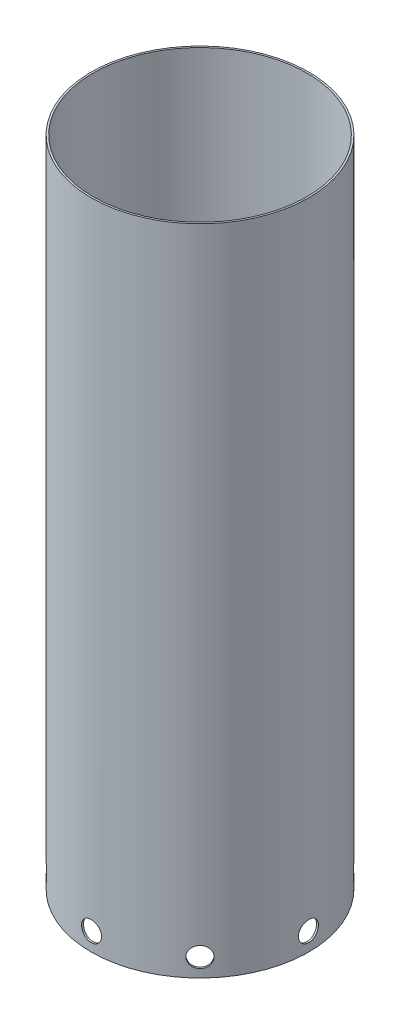
SolidWorks part; units mm, degrees
ref_plane "Front Plane" through (0, 0, 0) normal (0, 0, 1) x (1, 0, 0)
ref_plane "Top Plane" through (0, 0, 0) normal (0, 1, 0) x (1, 0, 0)
ref_plane "Right Plane" through (0, 0, 0) normal (1, 0, 0) x (0, 0, -1)
sketch "Sketch2" plane through (0, 0, 0) normal (0, 1, 0) x (1, 0, 0)
  circle A0 centre (0, 0) radius 74.93
  circle A1 centre (0, 0) radius 76.2
  dimension "D1" = 152.4
  dimension "D2" = 1.27
extrude "Boss-Extrude1" add sketch "Sketch2" along normal blind 457.2
sketch "Sketch3" plane through (0, 101.6, 0) normal (1, 0, 0) x (0, 0, -1)
  circle A0 centre (0, -38.1) radius 5.715 construction
  circle A1 centre (0, -38.1) radius 5.715 construction
  circle A2 centre (0, -38.1) radius 6.985
  dimension "D1" = 1.27
extrude "LOX to Kero, LOX Side Holes" [suppressed] cut sketch "Sketch3" along normal up to surface (75.8792 mm away)
pattern_circular "CirPattern1" [suppressed] count 8 over 360
sketch "Sketch4" plane through (0, -25.4, 0) normal (1, 0, 0) x (0, 0, 1)
  circle A0 centre (0, -38.1) radius 5.715 construction
  circle A1 centre (0, -38.1) radius 5.715 construction
  circle A2 centre (0, -38.1) radius 6.985
  dimension "D1" = 1.27
extrude "LOX to Kero, Kero Side Holes" [suppressed] cut sketch "Sketch4" along normal up to surface (75.8792 mm away)
pattern_circular "CirPattern2" [suppressed] count 8 over 360
sketch "Sketch5" plane through (0, -25.4, 0) normal (1, 0, 0) x (0, 0, 1)
  circle A0 centre (0, -38.1) radius 5.715 construction
  circle A1 centre (0, -38.1) radius 5.715 construction
  circle A2 centre (0, -38.1) radius 6.985
  dimension "D1" = 1.27
extrude "N2 to LOX, LOX Side Holes" cut sketch "Sketch5" along normal up to surface (75.8792 mm away) contours A2
pattern_circular "CirPattern3" count 8 over 360 about axis through (0, 0, 0) along (0, 1, 0) of "N2 to LOX, LOX Side Holes"
